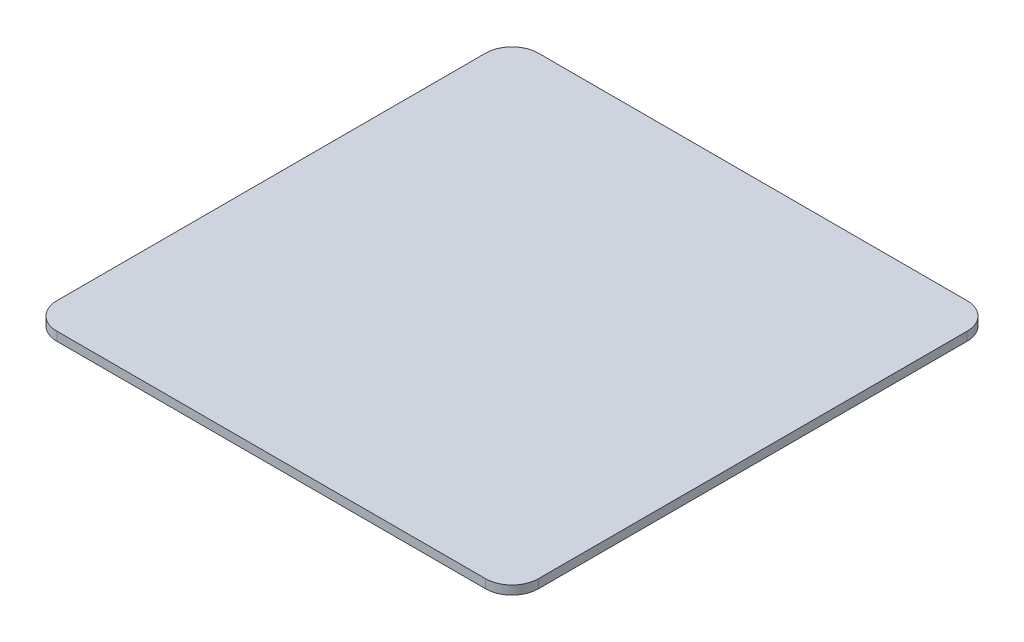
SolidWorks part; units mm, degrees
material "Aleación 1060"
ref_plane "Alzado" through (0, 0, 0) normal (0, 0, 1) x (1, 0, 0)
ref_plane "Planta" through (0, 0, 0) normal (0, 1, 0) x (1, 0, 0)
ref_plane "Vista lateral" through (0, 0, 0) normal (1, 0, 0) x (0, 0, -1)
ref_plane "Plano1" through (0, 54.7071, 0) normal (0, 1, 0) x (1, 0, 0)
sketch "Croquis1" plane through (0, 54.7071, 0) normal (0, 1, 0) x (1, 0, 0)
  line L12 (-178.357, -508.9955) -> (-178.357, -477.9)
  line L13 (-178.357, -477.9) -> (24.153, -477.9)
  line L14 (24.153, -477.9) -> (24.153, -508.9955)
  line L15 (24.153, -508.9955) -> (117.898, -508.9955)
  line L16 (141.8935, -485) -> (141.8935, -95)
  line L17 (117.898, -71.0045) -> (24.153, -71.0045)
  line L18 (24.153, -71.0045) -> (24.153, -102.1)
  line L19 (24.153, -102.1) -> (-178.357, -102.1)
  line L20 (-178.357, -102.1) -> (-178.357, -71.0045)
  line L21 (-178.357, -71.0045) -> (-272.102, -71.0045)
  line L22 (-296.0976, -95) -> (-296.0976, -485)
  line L23 (-272.102, -508.9955) -> (-178.357, -508.9955)
  line L27 (-178.357, -508.9955) -> (117.898, -508.9955)
  line L28 (141.8935, -485) -> (141.8935, -95)
  line L29 (117.898, -71.0045) -> (24.153, -71.0045)
  line L33 (24.153, -71.0045) -> (-272.102, -71.0045)
  line L34 (-296.0976, -95) -> (-296.0976, -485)
  line L35 (-272.102, -508.9955) -> (-178.357, -508.9955)
  arc A8 (117.898, -508.9955) -> (141.8935, -485) centre (117.898, -485) ccw
  arc A9 (141.8935, -95) -> (117.898, -71.0045) centre (117.898, -95) ccw
  arc A10 (-272.102, -71.0045) -> (-296.0976, -95) centre (-272.102, -95) ccw
  arc A11 (-296.0976, -485) -> (-272.102, -508.9955) centre (-272.102, -485) ccw
  arc A12 (117.898, -508.9955) -> (141.8935, -485) centre (117.898, -485) ccw
  arc A13 (141.8935, -95) -> (117.898, -71.0045) centre (117.898, -95) ccw
  arc A14 (-272.102, -71.0045) -> (-296.0976, -95) centre (-272.102, -95) ccw
  arc A15 (-296.0976, -485) -> (-272.102, -508.9955) centre (-272.102, -485) ccw
  point P0 (167.898, -21.0045)
  dimension "D1" = 0
extrude "Saliente-Extruir1" add sketch "Croquis1" along normal mid plane 8
